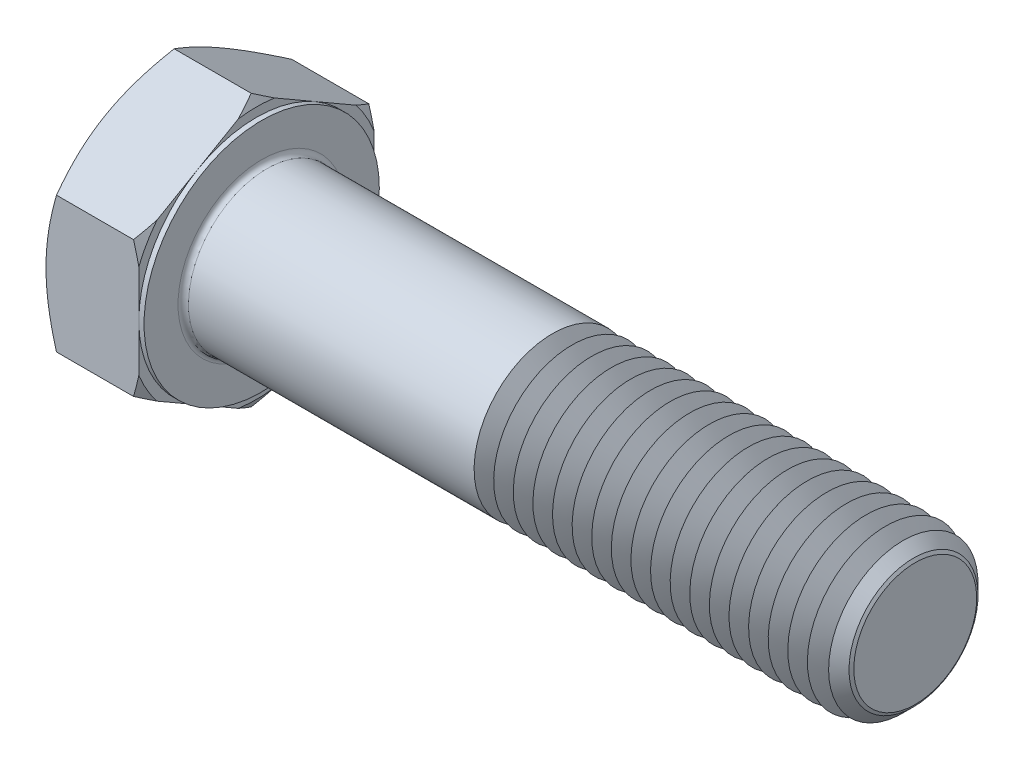
SolidWorks part; units mm, degrees
extrude "基体-拉伸" add sketch "草图1" along normal blind 15
sketch "草图1" plane through (0, 0, 0) normal (1, 0, 0) x (0, 0, -1)
  line L0 (18, 10.3923) -> (18, -10.3923)
  line L1 (-18, 10.3923) -> (-18, -10.3923)
  line L2 (18, -10.3923) -> (0, -20.7846)
  line L3 (0, -20.7846) -> (-18, -10.3923)
  line L4 (18, 10.3923) -> (0, 20.7846)
  line L5 (0, 20.7846) -> (-18, 10.3923)
  dimension "s" = 36
  dimension "D2" = 120
  dimension "D3" = 18
  dimension "D4" = 18
  dimension "D5" = 18
revolve "切除-旋转1" cut sketch "草图3" angle 360 about L6
sketch "草图3" plane through (0, 0, 0) normal (0, 0, 1) x (1, 0, 0)
  line L0 (0, 18) -> (4.4944, 25.7846)
  line L1 (0, 20.7846) -> (0, 10.3923) construction
  line L2 (4.4944, 25.7846) -> (4.4944, 30.7846)
  line L3 (4.4944, 30.7846) -> (-10, 30.7846)
  line L4 (-10, 30.7846) -> (-10, 18)
  line L5 (-10, 18) -> (0, 18)
  line L6 (0, 0) -> (99.06, 0) construction
  line L7 (15, 20.7846) -> (0, 20.7846) construction
  dimension "D1" = 18
  dimension "D2" = 5
  dimension "D3" = 10
  dimension "D4" = 5
  dimension "Head_ch_ang" = 30
ref_plane "前视" through (0, 0, 0) normal (0, 0, 1) x (1, 0, 0)
ref_plane "上视" through (0, 0, 0) normal (0, 1, 0) x (1, 0, 0)
ref_plane "右视" through (0, 0, 0) normal (1, 0, 0) x (0, 0, -1)
sketch "草图2" plane through (0, 0, 0) normal (0, 0, 1) x (1, 0, 0)
  line L0 (0, 10.3923) -> (0, -10.3923) construction
  line L1 (0, 0) -> (115, 0)
  line L2 (0, 0) -> (0, 12)
  line L3 (0, 12) -> (27.8072, 12)
  line L4 (115, 0) -> (115, 9.402)
  line L5 (15, 20.7846) -> (15, 10.3923) construction
  line L7 (0, 0) -> (96.52, 0) construction
  line L8 (115, -9.402) -> (27.8072, -12) construction
  line L9 (0, -12) -> (27.8072, -12) construction
  line L10 (18, 15.24) -> (18, -1.27) construction
  line L11 (61, 15.24) -> (61, -1.27) construction
  line L12 (15, 10.3923) -> (15, -10.3923) construction
  line L13 (27.8072, 12) -> (115, 12)
  line L14 (115, 12) -> (115, 9.402)
revolve "凸台-旋转1" add sketch "草图2" angle 360 about L7
cosmetic thread "螺旋线1" parameters "Thread_length"=54, "Thread_minor"=18.804
sketch "草图5" plane through (0, 0, 0) normal (0, 0, 1) x (1, 0, 0)
  line L0 (15, 18) -> (10.5056, 25.7846)
  line L1 (15, 20.7846) -> (15, 10.3923) construction
  line L2 (10.5056, 25.7846) -> (10.5056, 30.7846)
  line L3 (10.5056, 30.7846) -> (20.5056, 30.7846)
  line L4 (20.5056, 30.7846) -> (20.5056, 18)
  line L5 (20.5056, 18) -> (15, 18)
  line L7 (15, 20.7846) -> (1.6077, 20.7846) construction
  line L8 (0, 0) -> (99.06, 0) construction
  line L9 (0, 0) -> (99.06, 0) construction
  dimension "D1" = 18
  dimension "D2" = 5
  dimension "D3" = 10
  dimension "D4" = 5
revolve "切除-旋转2" cut sketch "草图5" angle 360 about L8
sketch "草图4" plane through (0, 0, 0) normal (0, 0, 1) x (1, 0, 0)
  line L1 (15, 20.7846) -> (15, 10.3923) construction
  line L2 (15, 18) -> (14.2, 18)
  line L3 (15, 18) -> (15, 30.7846)
  line L4 (15, 30.7846) -> (14.2, 30.7846)
  line L5 (0, 0) -> (95.25, 0) construction
  line L6 (0, 0) -> (96.52, 0) construction
  line L7 (14.2, 18) -> (14.2, 30.7846)
  line L8 (13.3923, 20.7846) -> (1.6077, 20.7846) construction
  dimension "D2" = 10
  dimension "D1" = 36
revolve "切除-旋转3" cut sketch "草图4" angle 360 about L5
chamfer "倒角" distance 2.4 angle 45 1 edges at (115, 0, 12)
fillet "圆角" radius 0.8 1 edges at (15, 0, -12)
sketch "草图6" plane through (0, 0, 0) normal (0, 0, 1) x (1, 0, 0)
  line L0 (61, -9.402) -> (59.5, -12)
  line L1 (61, -9.402) -> (62.5, -12)
  line L2 (62.5, -12) -> (62.5, -15)
  line L3 (-3.175, 0) -> (5.1513, 0) construction
  line L5 (62.5, -15) -> (59.5, -15)
  line L6 (59.5, -15) -> (59.5, -12)
  dimension "Thread_minor" = 18.804
  dimension "Diameter" = 24
  dimension "Start" = 61
revolve "切除-旋转4" cut sketch "草图6" angle 360 about L3
pattern_linear "阵列(线性)1" count 19 spacing 3 along (1, 0, 0) of "切除-旋转4"
equation "\"D3@草图1\" = \"s@草图1\" / 2"
equation "\"D4@草图1\" = \"D3@草图1\""
equation "\"D5@草图1\" = \"D4@草图1\""
equation "\"Thread_minor@螺旋线1\" = \"Minor_dia@草图2\""
equation "\"D1@草图3\" = \"s@草图1\" / 2"
equation "\"D1@草图5\" = \"s@草图1\" / 2"
equation "\"Head_ch_ang@草图5\" = \"Head_ch_ang@草图3\""
equation "\"D1@草图4\" = \"s@草图1\""
equation "\"Thread_length@螺旋线1\" = ((sgn( (\"l@草图2\" - \"p@草图2\" ) - \"h@草图2\" )-1)*( (\"l@草图2\" - \"p@草图2\" ) - \"h@草图2\" ))/-2+ \"h@草图2\""
equation "\"Thread_minor@草图6\" = \"Minor_dia@草图2\""
equation "\"Diameter@草图6\" = \"m@草图2\""
equation "\"Overcut@草图6\" = \"m@草图2\" * 1.25"
equation "\"Start@草图6\" = \"k@基体-拉伸\" + \"l@草图2\" - \"Thread_length@螺旋线1\"  '---Non-countersunk---"
equation "\"Num_threads@阵列(线性)1\" = int( \"Thread_length@螺旋线1\" / \"p@草图2\" + 0.999 )  + 1"
equation "\"Advance@阵列(线性)1\" = \"Thread_length@螺旋线1\" /  (\"Num_threads@阵列(线性)1\" - 1) 'relax it"
equation "\"Num_threads@阵列(线性)1\" = \"Num_threads@阵列(线性)1\" - sgn( \"Num_threads@阵列(线性)1\" - 1) '---chamfered tips only---"
equation "\"Minor_dia@草图2\" = \"m@草图2\"-\"p@草图2\" * 1.732"
equation "\"D1@倒角\" = \"p@草图2\"*0.8"
